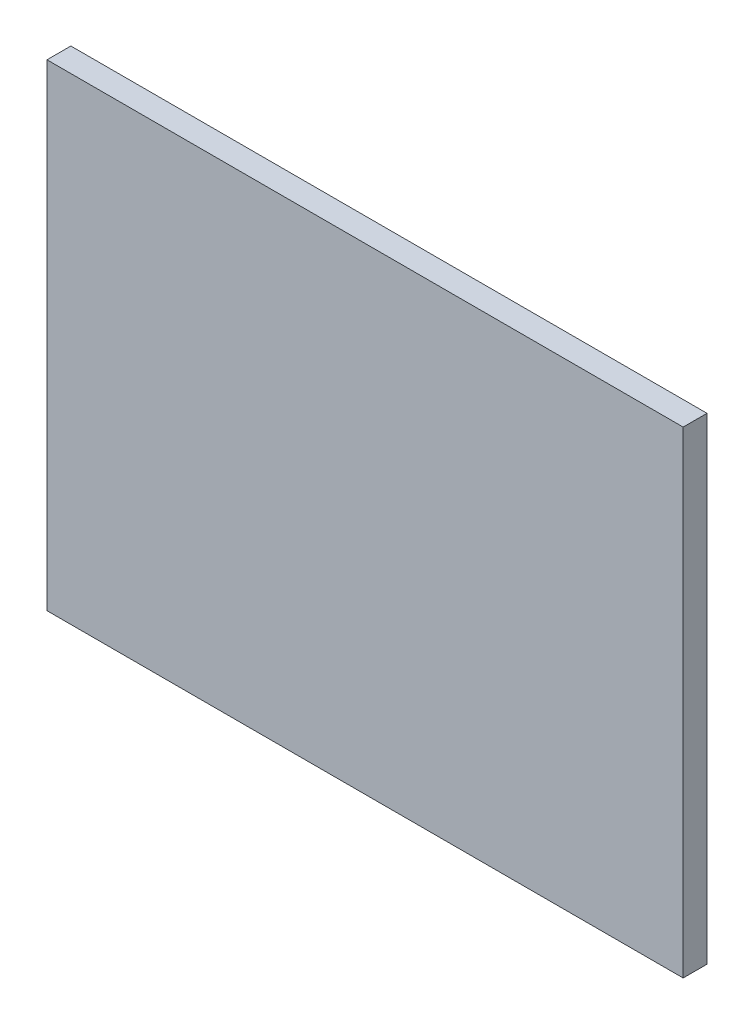
SolidWorks part; units mm, degrees
ref_plane "Plan de face" through (0, 0, 0) normal (0, 0, 1) x (1, 0, 0)
ref_plane "Plan de dessus" through (0, 0, 0) normal (0, 1, 0) x (1, 0, 0)
ref_plane "Plan de droite" through (0, 0, 0) normal (1, 0, 0) x (0, 0, -1)
sketch "Esquisse1" plane through (0, 0, 0) normal (0, 0, 1) x (1, 0, 0)
  line L1 (-67.0187, -15.3482) -> (12.9813, -15.3482)
  line L2 (-67.0187, -15.3482) -> (-67.0187, 44.6518)
  line L3 (-67.0187, 44.6518) -> (12.9813, 44.6518)
  line L4 (12.9813, -15.3482) -> (12.9813, 44.6518)
  dimension "D1" = 80
  dimension "D2" = 60
extrude "Boss.-Extru.1" add sketch "Esquisse1" along normal blind 3
